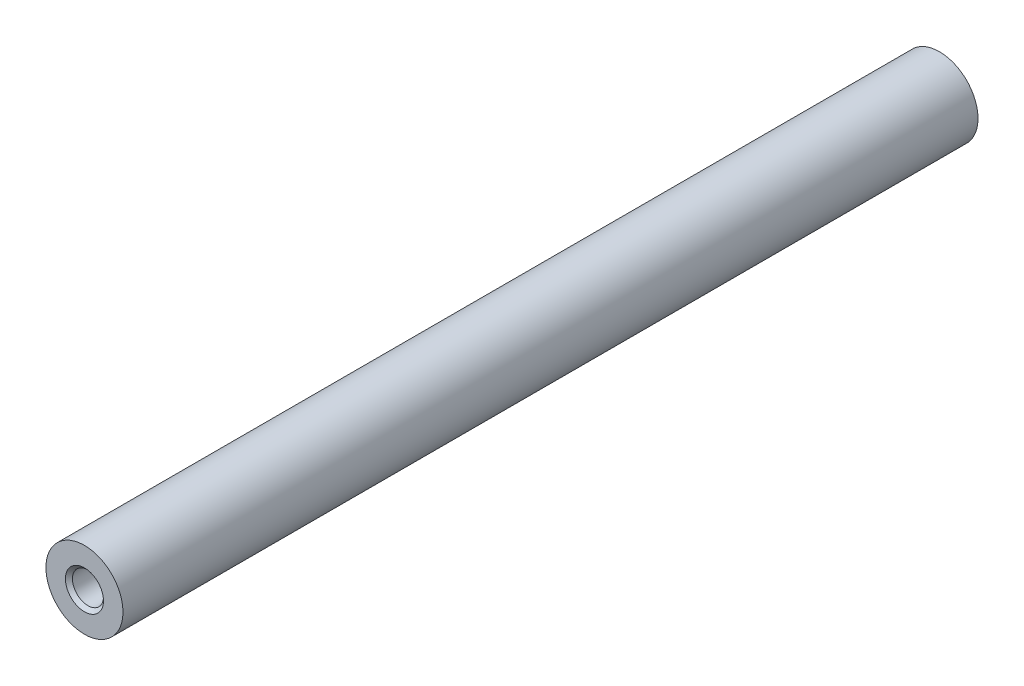
SolidWorks part; units mm, degrees
ref_plane "Plano frontal" through (0, 0, 0) normal (0, 0, 1) x (1, 0, 0)
ref_plane "Plano superior" through (0, 0, 0) normal (0, 1, 0) x (1, 0, 0)
ref_plane "Plano direito" through (0, 0, 0) normal (1, 0, 0) x (0, 0, -1)
sketch "Esboço1" plane through (0, 0, 0) normal (0, 0, 1) x (1, 0, 0)
  circle A0 centre (-29.0717, 179.8739) radius 4.1 construction
  circle A1 centre (-29.0717, 179.8739) radius 4.1
extrude "Ressalto-extrusão1" add sketch "Esboço1" against normal up to surface (91 mm away)
hole_wizard "Furo roscado de M4x0.71" positions "Esboço2" profile "Esboço3" tap size "M4x0.7" standard "Ansi Metric"
sketch "Esboço2" plane through (0, 0, 0) normal (0, 0, 1) x (1, 0, 0)
  point P0 (-29.0717, 179.8739)
cosmetic thread "Rosca de furo1" parameters "D1"=8, "D2"=4
sketch "Esboço3" plane through (-29.0717, 179.8739, 0) normal (1, 0, 0) x (0, -1, 0)
  line L0 (0, 0) -> (0, 12.4914)
  line L1 (0, 12.4914) -> (1.65, 11.5)
  line L2 (1.65, 11.5) -> (1.65, 0.375)
  line L3 (1.65, 0.375) -> (2.025, 0)
  line L5 (2.025, 0) -> (0, 0)
  line L6 (-1.65, 0.375) -> (-2.025, 0) construction
  line L10 (0, 12.4914) -> (-1.65, 11.5) construction
  line L11 (0, -6.35) -> (0, 107.95) construction
  dimension "Tap Drill Dia." = 3.3
  dimension "Tap Drill Depth" = 11.5
  dimension "Near C'Sink Dia." = 4.05
  dimension "Near C'Sink Angle" = 90
  dimension "Drill Angle" = 118
hole_wizard "Furo roscado de M4x0.72" positions "Esboço4" profile "Esboço5" tap size "M4x0.7" standard "Ansi Metric"
sketch "Esboço4" plane through (0, 0, -91) normal (0, 0, -1) x (-1, 0, 0)
  point P0 (29.0717, 179.8739)
sketch "Esboço5" plane through (-29.0717, 179.8739, -91) normal (1, 0, 0) x (0, 1, 0)
  line L0 (0, 0) -> (0, 12.4914)
  line L1 (0, 12.4914) -> (1.65, 11.5)
  line L2 (1.65, 11.5) -> (1.65, 0.375)
  line L3 (1.65, 0.375) -> (2.025, 0)
  line L5 (2.025, 0) -> (0, 0)
  line L6 (-1.65, 0.375) -> (-2.025, 0) construction
  line L10 (0, 12.4914) -> (-1.65, 11.5) construction
  line L11 (0, -6.35) -> (0, 107.95) construction
  dimension "Tap Drill Dia." = 3.3
  dimension "Tap Drill Depth" = 11.5
  dimension "Near C'Sink Dia." = 4.05
  dimension "Near C'Sink Angle" = 90
  dimension "Drill Angle" = 118
cosmetic thread "Rosca de furo2" parameters "D1"=8, "D2"=4
